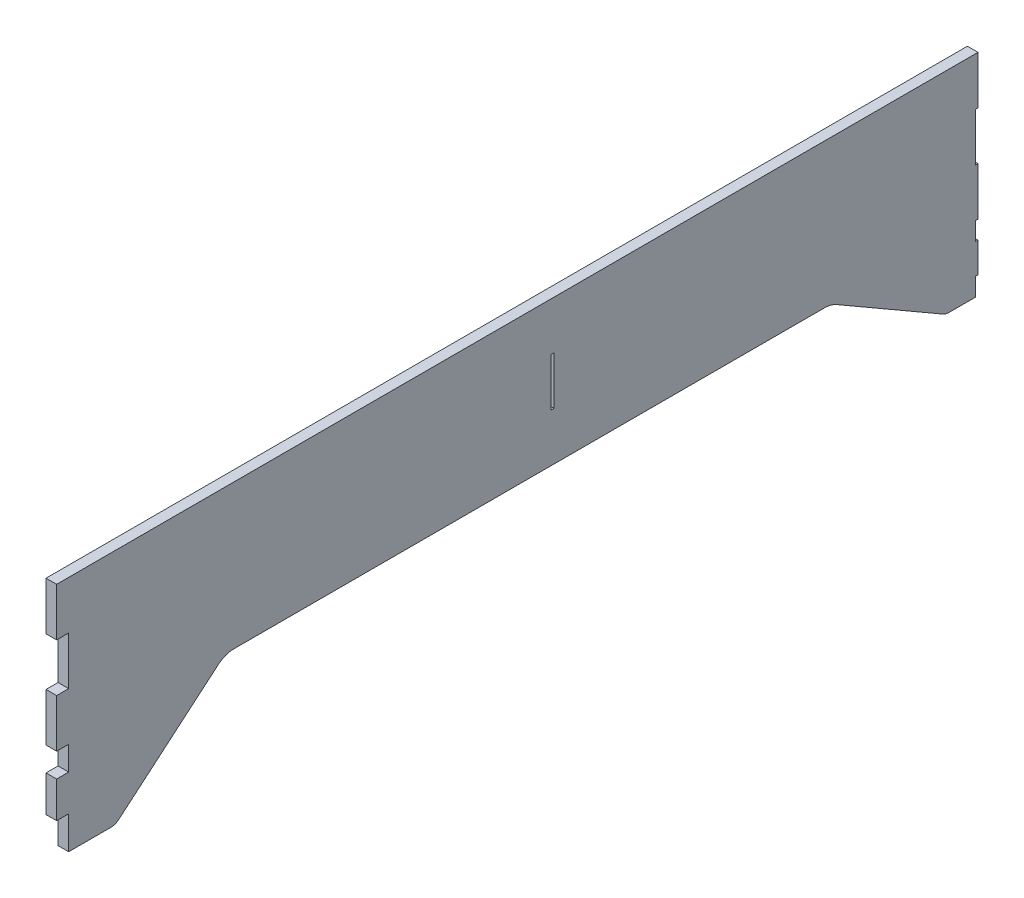
SolidWorks part; units mm, degrees
ref_plane "Front Plane" through (0, 0, 0) normal (0, 0, 1) x (1, 0, 0)
ref_plane "Top Plane" through (0, 0, 0) normal (0, 1, 0) x (1, 0, 0)
ref_plane "Right Plane" through (0, 0, 0) normal (1, 0, 0) x (0, 0, -1)
ref_plane "Plane1" through (-94.488, 0, 0) normal (-1, 0, 0) x (0, -1, 0)
sketch "Sketch1" plane through (-94.488, 0, 0) normal (-1, 0, 0) x (0, -1, 0)
  line L0 (111.125, -459.075) -> (85.725, -459.075)
  line L1 (85.725, -459.075) -> (85.725, -457.4875)
  line L2 (85.725, -457.4875) -> (111.125, -457.4875)
  line L3 (111.125, -457.4875) -> (111.125, -459.075)
  line L4 (111.125, -203.2) -> (85.725, -203.2)
  line L5 (85.725, -203.2) -> (85.725, -196.85)
  line L6 (85.725, -196.85) -> (60.325, -196.85)
  line L7 (60.325, -196.85) -> (60.325, -682.625)
  line L8 (60.325, -682.625) -> (85.725, -682.625)
  line L9 (85.725, -682.625) -> (85.725, -681.325)
  line L10 (85.725, -681.325) -> (111.125, -681.325)
  line L11 (111.125, -681.325) -> (111.125, -682.625)
  line L12 (111.125, -682.625) -> (136.525, -682.625)
  line L13 (136.525, -682.625) -> (136.525, -196.85)
  line L14 (136.525, -196.85) -> (111.125, -196.85)
  line L15 (111.125, -196.85) -> (111.125, -203.2)
  line L16 (136.525, -196.85) -> (185.6232, -196.85) construction
  line L17 (185.6232, -196.85) -> (185.6232, -227.7965) construction
  line L18 (184.1182, -229.5729) -> (139.535, -282.1971)
  line L19 (136.525, -203.2) -> (149.225, -203.2)
  line L20 (149.225, -203.2) -> (149.225, -196.85)
  line L21 (168.275, -196.85) -> (168.275, -203.2)
  line L22 (168.275, -203.2) -> (185.6232, -203.2)
  line L23 (185.6232, -203.2) -> (185.6232, -225.4683)
  line L24 (168.275, -196.85) -> (149.225, -196.85)
  line L25 (136.525, -681.325) -> (146.05, -681.325)
  line L26 (146.05, -681.325) -> (146.05, -682.625)
  line L27 (146.05, -682.625) -> (161.925, -682.625)
  line L28 (161.925, -682.625) -> (161.925, -681.325)
  line L29 (161.925, -681.325) -> (171.45, -681.325)
  line L30 (171.45, -681.325) -> (171.45, -667.3184)
  line L31 (170.5993, -664.1434) -> (138.2265, -608.072)
  circle A0 centre (130.175, -666.75) radius 1.7526 construction
  circle A1 centre (130.175, -615.95) radius 1.7526 construction
  circle A2 centre (130.175, -565.15) radius 1.7526 construction
  circle A3 centre (130.175, -514.35) radius 1.7526 construction
  circle A4 centre (130.175, -463.55) radius 1.7526 construction
  circle A5 centre (130.175, -412.75) radius 1.7526 construction
  circle A6 centre (130.175, -361.95) radius 1.7526 construction
  circle A7 centre (130.175, -311.15) radius 1.7526 construction
  circle A8 centre (130.175, -260.35) radius 1.7526 construction
  circle A9 centre (130.175, -209.55) radius 1.7526 construction
  arc A10 (184.1182, -229.5729) -> (185.6232, -225.4683) centre (179.2732, -225.4683) ccw
  arc A11 (139.535, -282.1971) -> (136.525, -290.4065) centre (149.225, -290.4065) ccw
  arc A12 (136.525, -601.722) -> (138.2265, -608.072) centre (149.225, -601.722) ccw
  arc A13 (171.45, -667.3184) -> (170.5993, -664.1434) centre (165.1, -667.3184) ccw
  point P38 (136.525, -285.75)
  point P58 (136.525, -605.125)
  dimension "D14" = 12.7
  dimension "D15" = 6.35
  dimension "D21" = 12.7
  dimension "D22" = 6.35
  dimension "D1" = 222.25
  dimension "D2" = 485.775
  dimension "D3" = 76.2
  dimension "D4" = 1.3
  dimension "D5" = 6.35
  dimension "D6" = 25.4
  dimension "D7" = 25.4
  dimension "D8" = 1.5875
  dimension "D9" = 49.0982
  dimension "D10" = 82.55
  dimension "D11" = 40.271
  dimension "D12" = 19.05
  dimension "D13" = 12.7
  dimension "D16" = 9.525
  dimension "D17" = 34.925
  dimension "D18" = 15.875
  dimension "D19" = 30
  dimension "D20" = 76.2
  dimension "D23" = 1.3
extrude "Boss-Extrude1" add sketch "Sketch1" against normal blind 5.588
